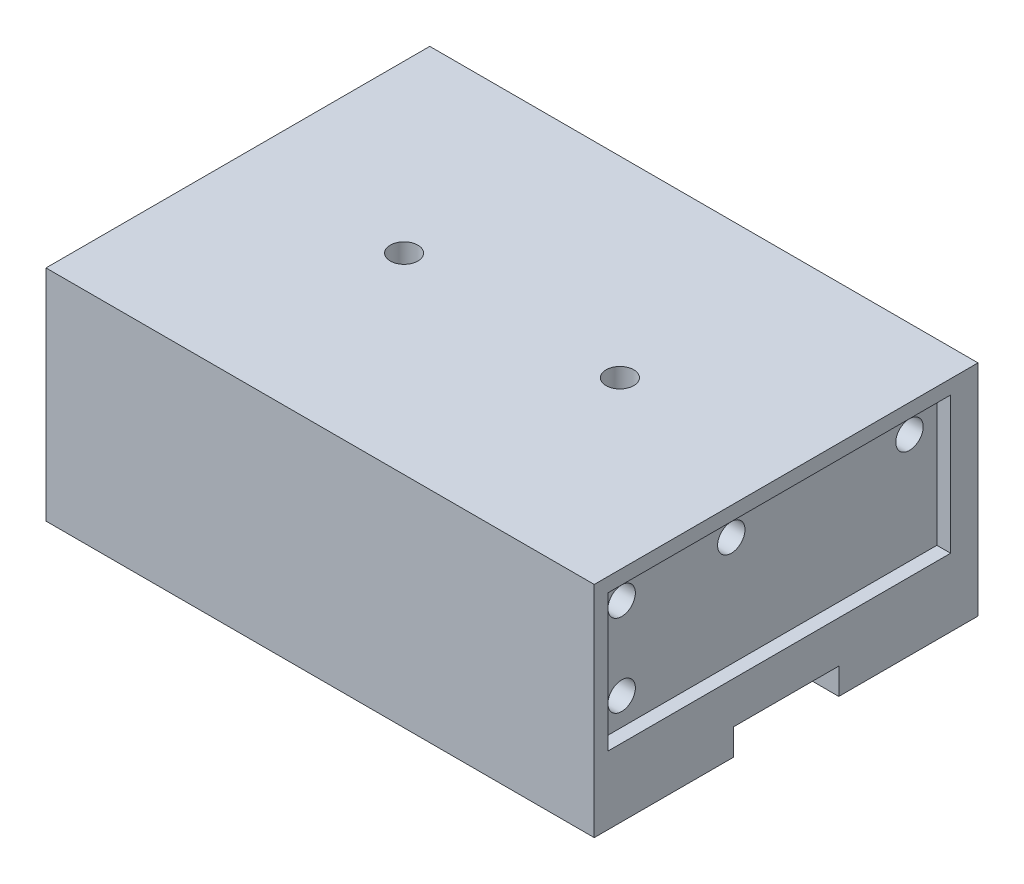
SolidWorks part; units mm, degrees
material "PETG"
ref_plane "Front Plane" through (0, 0, 0) normal (0, 0, 1) x (1, 0, 0)
ref_plane "Top Plane" through (0, 0, 0) normal (0, 1, 0) x (1, 0, 0)
ref_plane "Right Plane" through (0, 0, 0) normal (1, 0, 0) x (0, 0, -1)
sketch "Sketch2" plane through (0, 0, 0) normal (0, 1, 0) x (1, 0, 0)
  line L1 (-31.75, -22.225) -> (31.75, -22.225)
  line L2 (-31.75, -22.225) -> (-31.75, 22.225)
  line L3 (-31.75, 22.225) -> (31.75, 22.225)
  line L4 (31.75, -22.225) -> (31.75, 22.225)
  line L5 (-31.75, -22.225) -> (31.75, 22.225) construction
  line L6 (-31.75, 22.225) -> (31.75, -22.225) construction
  point P0 (0, 0)
  dimension "1.50" = 44.45
  dimension "D2" = 63.5
extrude "Boss-Extrude1" add sketch "Sketch2" along normal blind 25.4
sketch "Sketch3" plane through (0, 0, 0) normal (0, -1, 0) x (1, 0, 0)
  line L0 (31.75, 22.225) -> (31.75, -22.225) construction
  line L1 (-31.75, 6.1) -> (31.75, 6.1)
  line L2 (-31.75, 6.1) -> (-31.75, -6.1)
  line L3 (-31.75, -6.1) -> (31.75, -6.1)
  line L4 (31.75, 6.1) -> (31.75, -6.1)
  line L5 (-31.75, -22.225) -> (-31.75, 22.225) construction
  line L6 (-31.75, 0) -> (31.75, 0) construction
  point P12 (0, 0)
  dimension "D1" = 12.2
extrude "Cut-Extrude1" cut sketch "Sketch3" against normal blind 3.048
sketch "Sketch4" plane through (0, 25.4, 0) normal (0, 1, 0) x (1, 0, 0)
  line L0 (0, 22.225) -> (0, -22.225) construction
  line L1 (31.75, 22.225) -> (-31.75, 22.225) construction
  line L2 (-31.75, -22.225) -> (31.75, -22.225) construction
  line L3 (-31.75, 0) -> (31.75, 0) construction
  line L4 (-31.75, 22.225) -> (-31.75, -22.225) construction
  line L5 (31.75, -22.225) -> (31.75, 22.225) construction
  circle A0 centre (-12.5, 0) radius 1.6
  circle A1 centre (12.5, 0) radius 1.6
  dimension "D1" = 3.2
  dimension "D2" = 25
extrude "Cut-Extrude2" cut sketch "Sketch4" against normal through all
sketch "Sketch5" plane through (31.75, 1.541, -6.0579) normal (1, 0, 0) x (0, 0, -1)
  line L2 (-28.2829, 23.859) -> (-28.2829, -1.541) construction
  circle A0 centre (-23.5204, 19.05) radius 1.5875
  dimension "D1" = 3.175
  dimension "D2" = 4.7625
sketch "Sketch6" plane through (31.75, 1.541, -6.0579) normal (1, 0, 0) x (0, 0, -1)
  line L1 (-28.2829, 23.859) -> (-28.2829, -1.541) construction
  circle A0 centre (-23.5204, 9.525) radius 1.5875
  circle A1 centre (-23.5204, 19.05) radius 1.5875 construction
  dimension "D1" = 3.175
  dimension "D2" = 9.525
  dimension "D3" = 4.7625
sketch "Sketch8" plane through (31.75, 1.541, -6.0579) normal (1, 0, 0) x (0, 0, -1)
  circle A0 centre (-10.8204, 19.05) radius 1.5875
  dimension "D1" = 3.175
  dimension "D2" = 12.7
sketch "Sketch10" plane through (31.75, 0, 0) normal (1, 0, 0) x (0, 0, -1)
  circle A0 centre (15.875, 20.591) radius 1.5875
  circle A1 centre (-4.7625, 20.591) radius 1.5875 construction
  dimension "D1" = 3.175
  dimension "D2" = 20.6375
extrude "Cut-Extrude3" cut sketch "Sketch10" against normal blind 6.35 contours A0
extrude "Cut-Extrude4" cut sketch "Sketch8" against normal blind 6.35 contours A0
extrude "Cut-Extrude5" cut sketch "Sketch5" against normal blind 6.35 contours A0
extrude "Cut-Extrude6" cut sketch "Sketch6" against normal blind 6.35 contours A0
sketch "Sketch11" plane through (31.75, 1.541, -6.0579) normal (1, 0, 0) x (0, 0, -1)
  line L1 (-26.6954, 22.225) -> (12.9921, 22.225)
  line L2 (-26.6954, 22.225) -> (-26.6954, 6.35)
  line L3 (-26.6954, 6.35) -> (12.9921, 6.35)
  line L4 (12.9921, 22.225) -> (12.9921, 6.35)
  line L6 (-28.2829, 23.859) -> (-28.2829, -1.541) construction
  circle A0 centre (9.8171, 19.05) radius 1.5875 construction
  circle A1 centre (-23.5204, 9.525) radius 1.5875 construction
  dimension "D4" = 3.175
  dimension "D1" = 1.5875
  dimension "D3" = 3.175
extrude "Cut-Extrude8" cut sketch "Sketch11" against normal blind 1.5875
